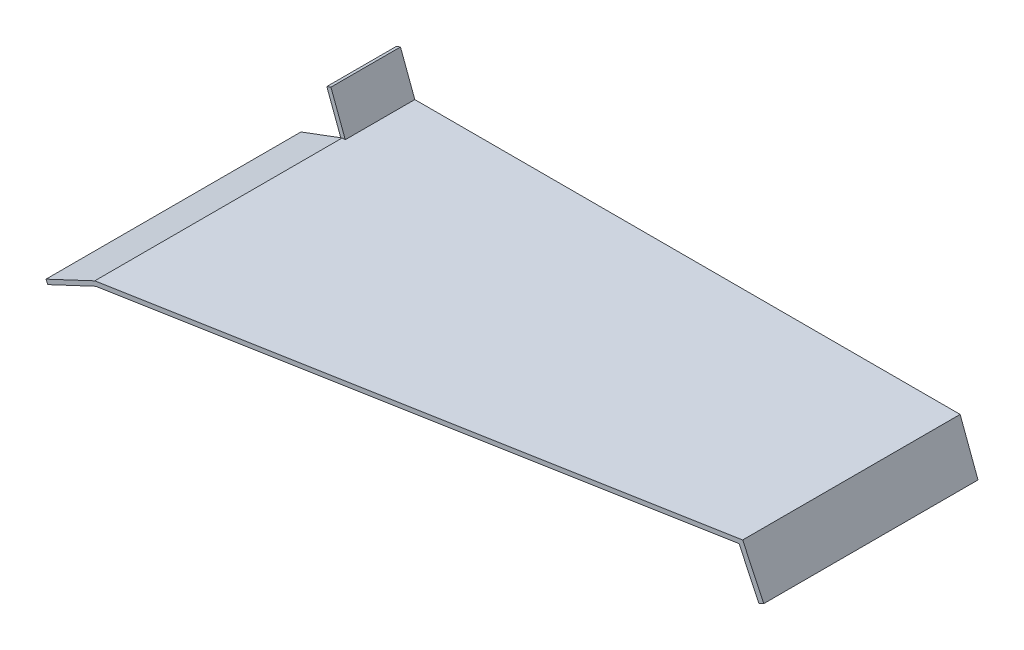
SolidWorks part; units mm, degrees
ref_plane "Front Plane" through (0, 0, 0) normal (0, 0, 1) x (1, 0, 0)
ref_plane "Top Plane" through (0, 0, 0) normal (0, 1, 0) x (1, 0, 0)
ref_plane "Right Plane" through (0, 0, 0) normal (1, 0, 0) x (0, 0, -1)
sketch "Sketch1" plane through (0, 0, 0) normal (0, 1, 0) x (1, 0, 0)
  line L1 (0, 0) -> (395.4099, 0)
  line L2 (0, 0) -> (0, 228.6)
  line L3 (0, 228.6) -> (395.4099, 228.6)
  line L4 (395.4099, 0) -> (395.4099, 228.6)
  dimension "D1" = 228.6
  dimension "D2" = 395.4099
extrude "Boss-Extrude1" add sketch "Sketch1" along normal blind 3.175
sketch "Sketch2" plane through (0, 3.175, 0) normal (0, 1, 0) x (1, 0, 0)
  line L0 (0, 0) -> (395.4099, 71.7959)
  line L1 (395.4099, 0) -> (395.4099, 228.6) construction
  line L2 (395.4099, 71.7959) -> (395.4099, 0)
  line L3 (395.4099, 0) -> (0, 0)
  dimension "D1" = 71.7959
extrude "Cut-Extrude1" cut sketch "Sketch2" against normal blind 3.175
sketch "Sketch3" plane through (0, 0, -228.6) normal (0, 0, -1) x (-1, 0, 0)
  line L0 (-395.4099, 3.175) -> (-408.296, -31.3271)
  line L1 (-408.296, -31.3271) -> (-405.3217, -32.438)
  line L2 (-405.3217, -32.438) -> (-392.0207, 3.175)
  line L3 (-395.4099, 3.175) -> (0, 3.175) construction
  line L4 (-392.0207, 3.175) -> (-395.4099, 3.175)
  line L5 (-395.4099, 0) -> (0, 0) construction
  dimension "D1" = 36.83
  dimension "D2" = 3.175
  dimension "D3" = 110.48
extrude "Boss-Extrude2" add sketch "Sketch3" against normal up to surface (155.0044 mm away)
sketch "Sketch4" plane through (0, 0, -228.6) normal (0, 0, -1) x (-1, 0, 0)
  line L0 (0, 0) -> (11.1087, 29.7432)
  line L1 (11.1087, 29.7432) -> (8.1344, 30.8541)
  line L2 (8.1344, 30.8541) -> (-3.3892, 0)
  line L3 (-393.2065, 0) -> (0, 0) construction
  line L4 (-3.3892, 0) -> (0, 0)
  line L5 (-395.4099, 3.175) -> (0, 3.175) construction
  dimension "D1" = 31.75
  dimension "D2" = 3.175
  dimension "D3" = 110.48
extrude "Boss-Extrude3" add sketch "Sketch4" against normal blind 50.165
sketch "Sketch6" plane through (0, 0, -178.435) normal (0, 0, 1) x (1, 0, 0)
  line L0 (0, 3.175) -> (-29.7432, -7.9337)
  line L1 (-29.7432, -7.9337) -> (-28.6324, -10.908)
  line L2 (-28.6324, -10.908) -> (9.0745, 3.175)
  line L3 (395.4099, 3.175) -> (0, 3.175) construction
  line L4 (9.0745, 3.175) -> (0, 3.175)
  line L5 (0, 0) -> (-11.1087, 29.7432) construction
  dimension "D1" = 31.75
  dimension "D2" = 3.175
  dimension "D3" = 90
extrude "Boss-Extrude5" add sketch "Sketch6" along normal up to surface (183.6339 mm away)
